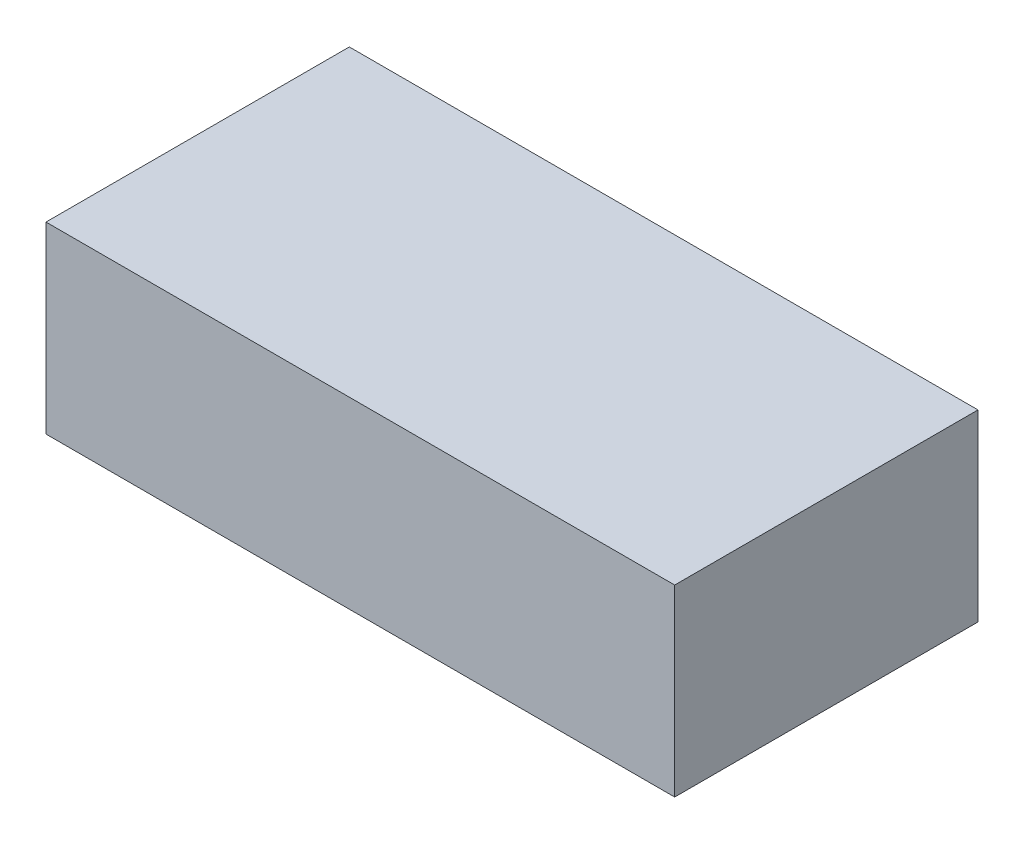
SolidWorks part; units mm, degrees
ref_plane "Front Plane" through (0, 0, 0) normal (0, 0, 1) x (1, 0, 0)
ref_plane "Top Plane" through (0, 0, 0) normal (0, 1, 0) x (1, 0, 0)
ref_plane "Right Plane" through (0, 0, 0) normal (1, 0, 0) x (0, 0, -1)
sketch "Sketch1" plane through (0, 0, 0) normal (0, 1, 0) x (1, 0, 0)
  line L1 (-36.195, -17.4625) -> (36.195, -17.4625)
  line L2 (-36.195, -17.4625) -> (-36.195, 17.4625)
  line L3 (-36.195, 17.4625) -> (36.195, 17.4625)
  line L4 (36.195, -17.4625) -> (36.195, 17.4625)
  line L5 (-36.195, -17.4625) -> (36.195, 17.4625) construction
  line L6 (-36.195, 17.4625) -> (36.195, -17.4625) construction
  point P0 (0, 0)
  dimension "D1" = 72.39
  dimension "D2" = 34.925
extrude "Boss-Extrude1" add sketch "Sketch1" along normal blind 21.1455
